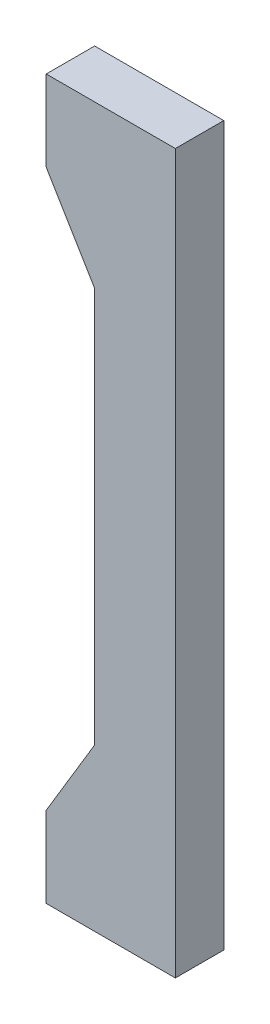
SolidWorks part; units mm, degrees
material "Pure Iron"
ref_plane "Front Plane" through (0, 0, 0) normal (0, 0, 1) x (1, 0, 0)
ref_plane "Top Plane" through (0, 0, 0) normal (0, 1, 0) x (1, 0, 0)
ref_plane "Right Plane" through (0, 0, 0) normal (1, 0, 0) x (0, 0, -1)
sketch "Sketch1" plane through (0, 0, 0) normal (0, 0, 1) x (1, 0, 0)
  line L0 (0, 62.2113) -> (0, -59.4344) construction
  line L1 (-71.393, 0) -> (18.2737, 0) construction
  line L2 (-80, 222.5) -> (0, 222.5)
  line L3 (0, 222.5) -> (0, -222.5)
  line L4 (-80, 222.5) -> (-80, 172.5)
  line L5 (-80, 172.5) -> (-50, 122.5)
  line L6 (-50, 122.5) -> (-50, -122.5)
  line L7 (-80, -172.5) -> (-50, -122.5)
  line L8 (-80, -222.5) -> (-80, -172.5)
  line L9 (-80, -222.5) -> (0, -222.5)
  point P14 (-50, 0)
  point P17 (0, 0)
  dimension "D1" = 0
  dimension "D2" = 50
  dimension "D3" = 80
  dimension "D4" = 222.5
  dimension "D5" = 50
  dimension "D6" = 100
extrude "Boss-Extrude1" add sketch "Sketch1" along normal mid plane 30 contours L6 L7 L8 L9 L3 L2 L4 L5
